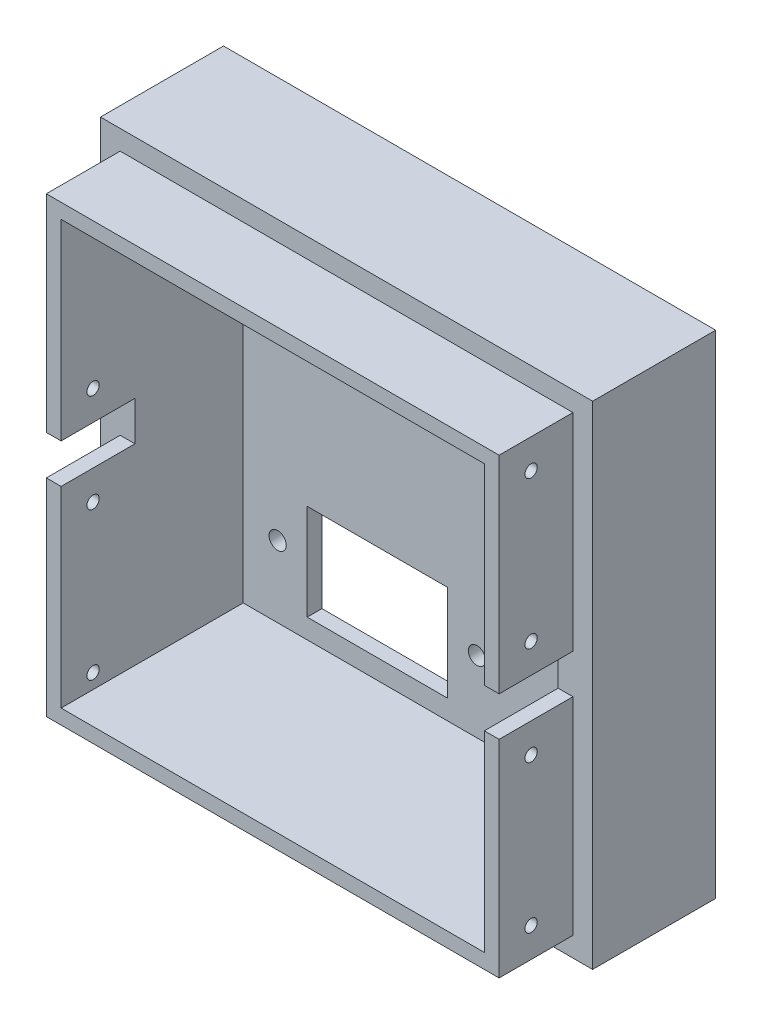
SolidWorks part; units mm, degrees
ref_plane "Płaszczyzna przednia" through (0, 0, 0) normal (0, 0, 1) x (1, 0, 0)
ref_plane "Płaszczyzna górna" through (0, 0, 0) normal (0, 1, 0) x (1, 0, 0)
ref_plane "Płaszczyzna prawa" through (0, 0, 0) normal (1, 0, 0) x (0, 0, -1)
sketch "Szkic1" plane through (0, 0, 0) normal (0, 0, 1) x (1, 0, 0)
  line L1 (0, 0) -> (100, 0)
  line L2 (0, 0) -> (0, 100)
  line L3 (0, 100) -> (100, 100)
  line L4 (100, 0) -> (100, 100)
  dimension "D1" = 100
  dimension "D2" = 100
extrude "Dodanie-wyciągnięcie1" add sketch "Szkic1" along normal blind 40
sketch "Szkic3" plane through (0, 0, 40) normal (0, 0, 1) x (1, 0, 0)
  line L1 (0, 0) -> (100, 0)
  line L2 (0, 0) -> (0, 100)
  line L3 (0, 100) -> (100, 100)
  line L4 (100, 0) -> (100, 100)
  line L5 (4, 4) -> (96, 4)
  line L6 (4, 4) -> (4, 96)
  line L7 (4, 96) -> (96, 96)
  line L8 (96, 4) -> (96, 96)
  dimension "D1" = 4
  dimension "D2" = 4
  dimension "D3" = 4
  dimension "D4" = 4
extrude "Wytnij-wyciągnięcie1" cut sketch "Szkic3" against normal blind 15
sketch "Szkic4" plane through (0, 0, 40) normal (0, 0, 1) x (1, 0, 0)
  line L0 (4, 96) -> (4, 4) construction
  line L1 (7, 93) -> (93, 93)
  line L2 (7, 93) -> (7, 7)
  line L3 (7, 7) -> (93, 7)
  line L4 (93, 93) -> (93, 7)
  line L5 (4, 4) -> (96, 4) construction
  line L6 (96, 4) -> (96, 96) construction
  line L7 (96, 96) -> (4, 96) construction
  dimension "D1" = 3
  dimension "D2" = 3
  dimension "D3" = 3
  dimension "D4" = 3
extrude "Wytnij-wyciągnięcie2" cut sketch "Szkic4" against normal blind 37
sketch "Szkic6" plane through (0, 0, 40) normal (0, 0, 1) x (1, 0, 0)
  line L0 (4, 96) -> (4, 4) construction
  line L1 (4, 54) -> (7, 54)
  line L2 (4, 54) -> (4, 46)
  line L3 (4, 46) -> (7, 46)
  line L4 (7, 54) -> (7, 46)
  line L5 (7, 93) -> (7, 7) construction
  line L6 (93, 7) -> (93, 93) construction
  line L7 (93, 54) -> (96, 54)
  line L8 (93, 54) -> (93, 46)
  line L9 (93, 46) -> (96, 46)
  line L10 (96, 54) -> (96, 46)
  line L11 (96, 4) -> (96, 96) construction
  line L12 (0, 0) -> (100, 0) construction
  dimension "D1" = 8
  dimension "D2" = 46
  dimension "D3" = 46
  dimension "D4" = 8
extrude "Wytnij-wyciągnięcie3" cut sketch "Szkic6" against normal blind 15
sketch "Szkic9" plane through (96, 0, 0) normal (1, 0, 0) x (0, 0, -1)
  line L0 (-25, 0) -> (-25, 100) construction
  line L1 (-25, 54) -> (-25, 96) construction
  line L2 (-25, 4) -> (-25, 46) construction
  line L3 (-25, 0) -> (0, 0) construction
  circle A0 centre (-33.5, 60) radius 1.25
  circle A1 centre (-33.5, 90) radius 1.25
  circle A2 centre (-33.5, 40) radius 1.25
  circle A3 centre (-33.5, 10) radius 1.25
  dimension "D5" = 2.5
  dimension "D6" = 2.5
  dimension "D7" = 2.5
  dimension "D8" = 2.5
  dimension "D1" = 8.5
  dimension "D2" = 8.5
  dimension "D3" = 8.5
  dimension "D4" = 8.5
  dimension "D9" = 10
  dimension "D10" = 40
  dimension "D11" = 60
  dimension "D12" = 90
extrude "Wytnij-wyciągnięcie4" cut sketch "Szkic9" against normal blind 100
sketch "Szkic10" plane through (0, 0, 0) normal (0, 0, -1) x (-1, 0, 0)
  line L0 (0, 0) -> (-100, 0) construction
  line L1 (-48.5, 30.5) -> (-20, 30.5)
  line L2 (-48.5, 30.5) -> (-48.5, 11)
  line L3 (-48.5, 11) -> (-20, 11)
  line L4 (-20, 30.5) -> (-20, 11)
  line L5 (0, 100) -> (0, 0) construction
  circle A0 centre (-54.5, 21.5) radius 1.75
  circle A1 centre (-14, 21.5) radius 1.75
  dimension "D7" = 3.5
  dimension "D8" = 3.5
  dimension "D1" = 9
  dimension "D2" = 9
  dimension "D3" = 19.5
  dimension "D4" = 28.5
  dimension "D5" = 6
  dimension "D6" = 6
  dimension "D9" = 11
  dimension "D10" = 20
extrude "Wytnij-wyciągnięcie5" cut sketch "Szkic10" against normal blind 10
sketch "Szkic11" plane through (0, 0, 0) normal (0, 0, -1) x (-1, 0, 0)
  line L0 (0, 0) -> (-100, 0) construction
  text T0 "by Jakub Kołodziej" font "Arial" height 6
  dimension "D1" = 50
extrude "Wytnij-wyciągnięcie6" cut sketch "Szkic11" against normal blind 2
sketch "Szkic12" plane through (0, 0, 0) normal (0, 0, -1) x (-1, 0, 0)
  line L0 (-100, 100) -> (0, 100) construction
  line L1 (-100, 0) -> (-100, 100) construction
  circle A0 centre (-76, 75) radius 6.5
  circle A1 centre (-83.2486, 82.2486) radius 1.25
  circle A2 centre (-68.7486, 82.2486) radius 1.25
  circle A3 centre (-83.2486, 67.7486) radius 1.25
  circle A4 centre (-68.7486, 67.7486) radius 1.25
  circle A5 centre (-55, 75) radius 6.5
  circle A6 centre (-62.2486, 82.2486) radius 1.25
  circle A7 centre (-47.7486, 82.2486) radius 1.25
  circle A8 centre (-62.2486, 67.7486) radius 1.25
  circle A9 centre (-47.7486, 67.7486) radius 1.25
  point P14 (-78.7478, 73.458)
  point P25 (0, 0)
  dimension "D1" = 13
  dimension "D8" = 2.5
  dimension "D9" = 2.5
  dimension "D10" = 2.5
  dimension "D11" = 2.5
  dimension "D14" = 13
  dimension "D21" = 2.5
  dimension "D22" = 2.5
  dimension "D23" = 2.5
  dimension "D24" = 2.5
  dimension "D2" = 14.5
  dimension "D3" = 14.5
  dimension "D4" = 14.5
  dimension "D5" = 14.5
  dimension "D6" = 20.5061
  dimension "D7" = 10.255
  dimension "D12" = 25
  dimension "D13" = 24
  dimension "D15" = 14.5
  dimension "D16" = 14.5
  dimension "D17" = 14.5
  dimension "D18" = 14.5
  dimension "D19" = 20.5061
  dimension "D20" = 10.255
  dimension "D25" = 25
  dimension "D26" = 45
extrude "Wytnij-wyciągnięcie7" cut sketch "Szkic12" against normal blind 3
sketch "Szkic13" plane through (0, 0, 0) normal (0, 0, -1) x (-1, 0, 0)
  line L0 (-100, 100) -> (0, 100) construction
  line L1 (-29.375, 84.25) -> (-16.375, 84.25)
  line L2 (-29.375, 84.25) -> (-29.375, 80.25)
  line L3 (-29.375, 80.25) -> (-16.375, 80.25)
  line L4 (-16.375, 84.25) -> (-16.375, 80.25)
  line L6 (0, 100) -> (0, 0) construction
  circle A1 centre (-31.375, 82.25) radius 1
  circle A2 centre (-14.375, 82.25) radius 1
  point P12 (0, 0)
  dimension "D3" = 17.75
  dimension "D7" = 2
  dimension "D8" = 2
  dimension "D1" = 13
  dimension "D2" = 4
  dimension "D4" = 16.375
  dimension "D5" = 17.75
  dimension "D6" = 15.75
  dimension "D9" = 2
  dimension "D10" = 2
extrude "Wytnij-wyciągnięcie8" cut sketch "Szkic13" against normal blind 3
